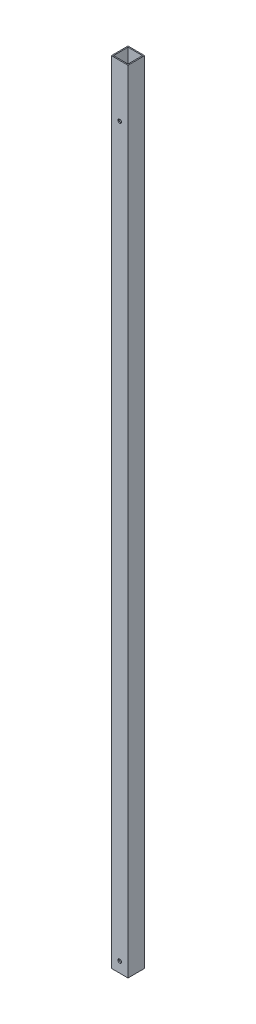
SolidWorks part; units mm, degrees
ref_plane "Front Plane" through (0, 0, 0) normal (0, 0, 1) x (1, 0, 0)
ref_plane "Top Plane" through (0, 0, 0) normal (0, 1, 0) x (1, 0, 0)
ref_plane "Right Plane" through (0, 0, 0) normal (1, 0, 0) x (0, 0, -1)
sketch "Sketch1" plane through (0, 0, 0) normal (0, 1, 0) x (1, 0, 0)
  line L0 (-6.9, -6.9) -> (-6.9, 6.9)
  line L1 (-7.9, -7.9) -> (7.9, -7.9)
  line L2 (-7.9, -7.9) -> (-7.9, 7.9)
  line L3 (-7.9, 7.9) -> (7.9, 7.9)
  line L4 (7.9, -7.9) -> (7.9, 7.9)
  line L5 (-7.9, -7.9) -> (7.9, 7.9) construction
  line L6 (-7.9, 7.9) -> (7.9, -7.9) construction
  line L7 (-6.9, 6.9) -> (6.9, 6.9)
  line L8 (6.9, -6.9) -> (6.9, 6.9)
  line L9 (-6.9, -6.9) -> (6.9, -6.9)
  point P0 (0, 0)
  dimension "D1" = 1
extrude "Boss-Extrude1" add sketch "Sketch1" along normal blind 750
sketch "Sketch3" plane through (0, 0, 7.9) normal (0, 0, 1) x (1, 0, 0)
  circle A1 centre (0, 10) radius 1.7
  circle A2 centre (0, 700) radius 1.7
  dimension "D1" = 3.4
  dimension "D2" = 3.4
  dimension "D3" = 10
extrude "Cut-Extrude1" cut sketch "Sketch3" against normal through all
